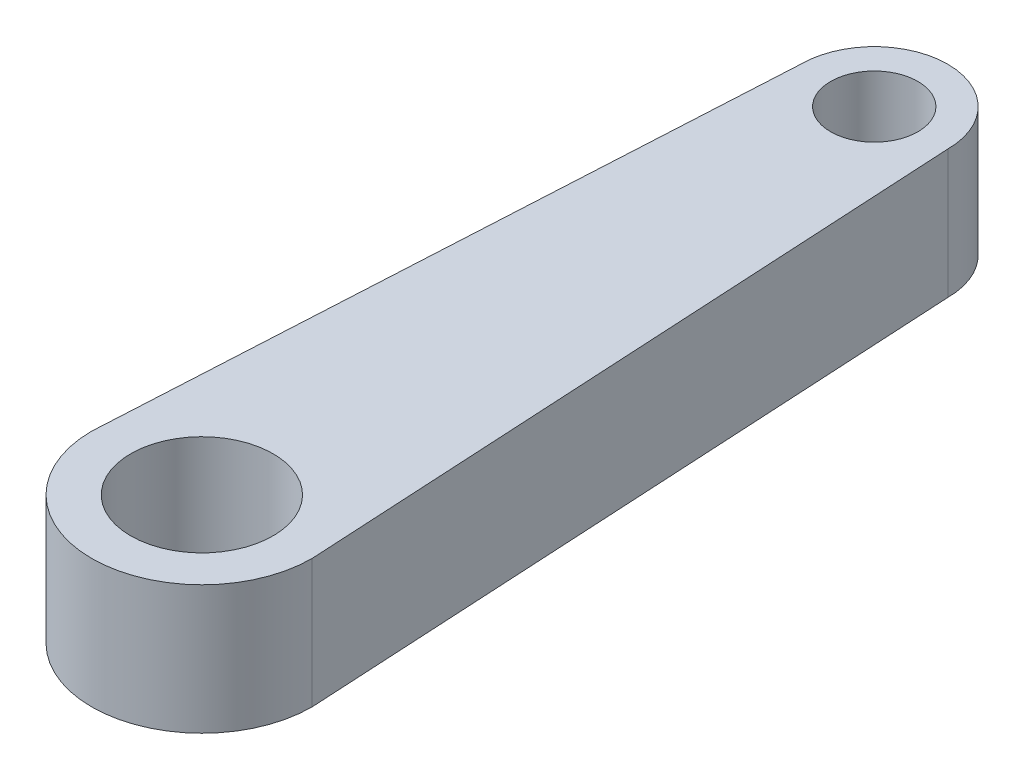
SolidWorks part; units mm, degrees
material "ASTM A36 Steel"
ref_plane "Front Plane" through (0, 0, 0) normal (0, 0, 1) x (1, 0, 0)
ref_plane "Top Plane" through (0, 0, 0) normal (0, 1, 0) x (1, 0, 0)
ref_plane "Right Plane" through (0, 0, 0) normal (1, 0, 0) x (0, 0, -1)
sketch "Sketch2" plane through (0, 0, 0) normal (0, 1, 0) x (1, 0, 0)
  line L0 (-10.0692, 0) -> (8.3219, 0) construction
  line L9 (-6, 0) -> (-4, 36.6)
  line L10 (6, 0) -> (4, 36.6)
  circle A0 centre (0, 0) radius 3.875
  arc A1 (-6, 0) -> (6, 0) centre (0, 0) ccw
  circle A3 centre (0, 36.6) radius 2.375
  arc A4 (4, 36.6) -> (-4, 36.6) centre (0, 36.6) ccw
  dimension "D1" = 7.75
  dimension "D3" = 4.75
  dimension "D2" = 8
  dimension "D4" = 6
  dimension "D5" = 36.6
extrude "Boss-Extrude1" add sketch "Sketch2" along normal blind 7
